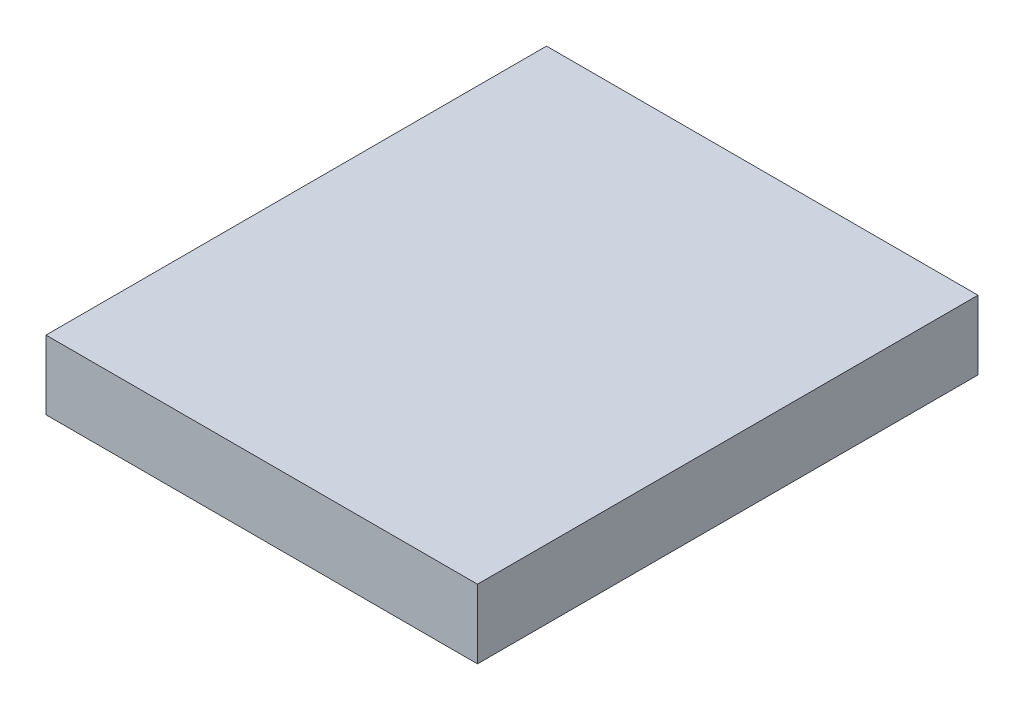
SolidWorks part; units mm, degrees
ref_plane "Front Plane" through (0, 0, 0) normal (0, 0, 1) x (1, 0, 0)
ref_plane "Top Plane" through (0, 0, 0) normal (0, 1, 0) x (1, 0, 0)
ref_plane "Right Plane" through (0, 0, 0) normal (1, 0, 0) x (0, 0, -1)
ref_plane "Plane1" through (0, 2.54, 0) normal (0, 1, 0) x (1, 0, 0)
sketch "Sketch1" plane through (0, 2.54, 0) normal (0, 1, 0) x (1, 0, 0)
  line L1 (79.375, 92.075) -> (-79.375, 92.075)
  line L2 (79.375, 92.075) -> (79.375, -92.075)
  line L3 (79.375, -92.075) -> (-79.375, -92.075)
  line L4 (-79.375, 92.075) -> (-79.375, -92.075)
  point P4 (0, -92.075)
  point P5 (79.375, 0)
  point P6 (0, 0)
  point P9 (0, 0)
  dimension "D1" = 158.75
  dimension "D2" = 184.15
extrude "Boss-Extrude1" add sketch "Sketch1" against normal blind 25.4
shell "Shell1" thickness 2.54
